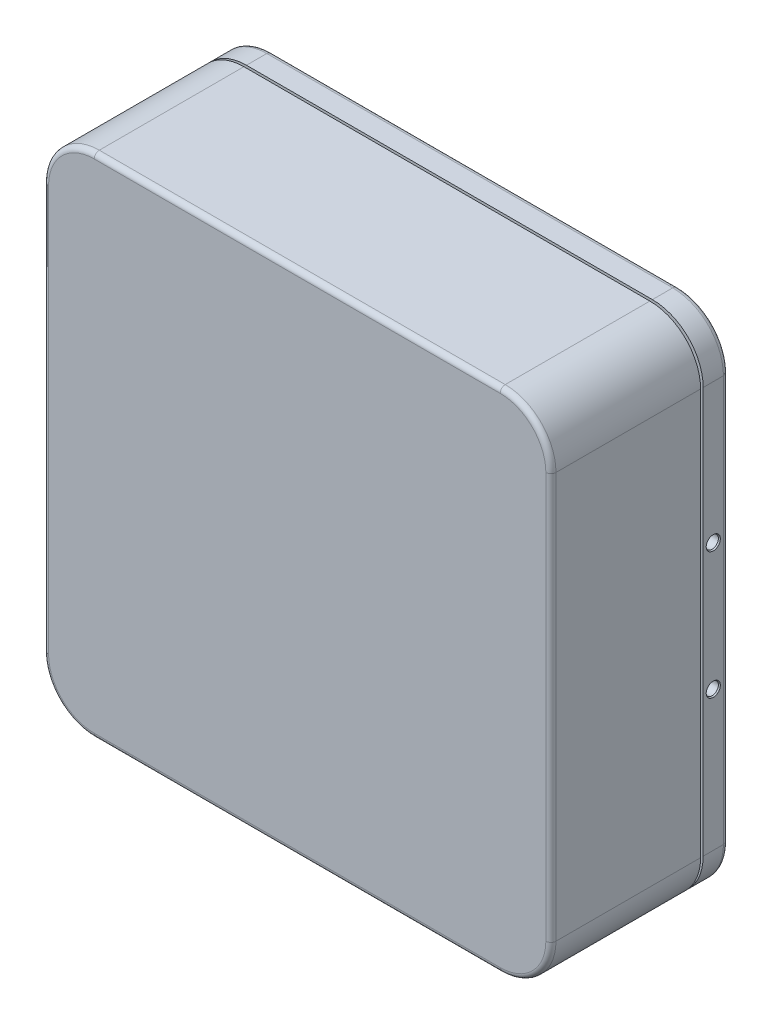
SolidWorks part; units mm, degrees
material "ABS"
ref_plane "Front Plane" through (0, 0, 0) normal (0, 0, 1) x (1, 0, 0)
ref_plane "Top Plane" through (0, 0, 0) normal (0, 1, 0) x (1, 0, 0)
ref_plane "Right Plane" through (0, 0, 0) normal (1, 0, 0) x (0, 0, -1)
sketch "Sketch1" plane through (0, 0, 0) normal (0, 0, 1) x (1, 0, 0)
  line L1 (0, 0) -> (200, 0)
  line L2 (0, 0) -> (0, 200)
  line L3 (0, 200) -> (200, 200)
  line L4 (200, 0) -> (200, 200)
  dimension "D1" = 200
  dimension "D2" = 200
extrude "Boss-Extrude1" add sketch "Sketch1" along normal blind 70 contours L3 L4 L1 L2
fillet "Fillet1" radius 20 4 edges at (200, 200, 35) (200, 0, 35) (0, 200, 35) (0, 0, 35)
fillet "Fillet2" radius 2 16 edges at (5.8579, 194.1421, 0) (0, 100, 0) (5.8579, 5.8579, 0) (100, 0, 0) (194.1421, 5.8579, 0) (200, 100, 0) (194.1421, 194.1421, 0) (100, 200, 0) (194.1421, 5.8579, 70) (100, 0, 70) (5.8579, 5.8579, 70) (0, 100, 70) (5.8579, 194.1421, 70) (100, 200, 70) (194.1421, 194.1421, 70) (200, 100, 70)
ref_plane "Plane1" through (0, 0, 10) normal (0, 0, -1) x (-1, 0, 0)
sketch "Sketch2" plane through (0, 0, 10) normal (0, 0, -1) x (-1, 0, 0)
  line L1 (-215.6402, 214.9587) -> (14.8154, 214.9587)
  line L2 (-215.6402, 214.9587) -> (-215.6402, -15.8492)
  line L3 (-215.6402, -15.8492) -> (14.8154, -15.8492)
  line L4 (14.8154, 214.9587) -> (14.8154, -15.8492)
  line L12 (-7, 20) -> (-7, 180)
  line L13 (-20, 193) -> (-180, 193)
  line L14 (-193, 180) -> (-193, 20)
  line L15 (-180, 7) -> (-20, 7)
  line L16 (-7, 20) -> (-7, 180)
  line L17 (-20, 193) -> (-180, 193)
  line L18 (-193, 180) -> (-193, 20)
  line L19 (-180, 7) -> (-20, 7)
  arc A8 (-7, 180) -> (-20, 193) centre (-20, 180) ccw
  arc A9 (-180, 193) -> (-193, 180) centre (-180, 180) ccw
  arc A10 (-193, 20) -> (-180, 7) centre (-180, 20) ccw
  arc A11 (-20, 7) -> (-7, 20) centre (-20, 20) ccw
  arc A12 (-7, 180) -> (-20, 193) centre (-20, 180) ccw
  arc A13 (-180, 193) -> (-193, 180) centre (-180, 180) ccw
  arc A14 (-193, 20) -> (-180, 7) centre (-180, 20) ccw
  arc A15 (-20, 7) -> (-7, 20) centre (-20, 20) ccw
  dimension "D1" = 5
extrude "Cut-Extrude1" cut sketch "Sketch2" against normal blind 1
sketch "Sketch3" plane through (0, 0, 0) normal (-1, 0, 0) x (0, 0, 1)
  line L0 (0, 100) -> (70, 100) construction
  line L1 (0, 20) -> (0, 180) construction
  line L2 (70, 180) -> (70, 20) construction
  circle A0 centre (6, 125) radius 2.5
  circle A1 centre (6, 75) radius 2.5
  dimension "D4" = 5
  dimension "D5" = 5
  dimension "D1" = 25
  dimension "D2" = 25
  dimension "D3" = 6
extrude "Cut-Extrude2" cut sketch "Sketch3" against normal blind 5
chamfer "Chamfer1" distance 0.5 angle 30 2 edges at (0, 75, 8.5) (0, 125, 8.5)
ref_plane "Plane2" through (100, 0, 0) normal (-1, 0, 0) x (0, 0, 1)
mirror "Mirror2" about plane through (100, 0, 0) normal (-1, 0, 0) of "Cut-Extrude2"
chamfer "Chamfer2" distance 0.5 angle 30 2 edges at (200, 75, 8.5) (200, 125, 8.5)
